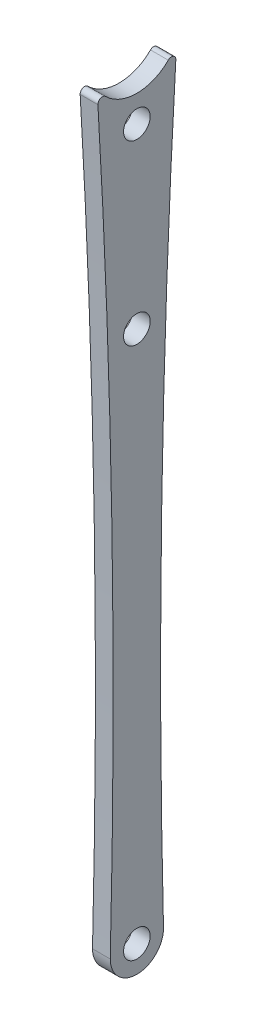
SolidWorks part; units mm, degrees
ref_plane "前视基准面" through (0, 0, 0) normal (0, 0, 1) x (1, 0, 0)
ref_plane "上视基准面" through (0, 0, 0) normal (0, 1, 0) x (1, 0, 0)
ref_plane "右视基准面" through (0, 0, 0) normal (1, 0, 0) x (0, 0, -1)
other "Configuration Table"
sketch "草图1" plane through (0, 0, 0) normal (1, 0, 0) x (0, 0, -1)
  line L0 (0, 0) -> (0, 88) construction
  arc A0 (-3, 0) -> (3, 0) centre (0, 0) ccw
  arc A1 (3, 0) -> (4.3906, 84.084) centre (1002.6743, 25.5202) cw
  arc A2 (4.3906, 84.084) -> (3.5377, 84.4667) centre (3.8915, 84.1133) ccw
  arc A3 (3.5377, 84.4667) -> (-3.5377, 84.4667) centre (0, 88) cw
  circle A4 centre (0, 80) radius 1.5
  circle A5 centre (0, 60) radius 1.5
  arc A6 (-4.3906, 84.084) -> (-3.5377, 84.4667) centre (-3.8915, 84.1133) cw
  arc A7 (-3, 0) -> (-4.3906, 84.084) centre (-1002.6743, 25.5202) ccw
  circle A8 centre (0, 0) radius 1.5
  dimension "D1" = 80
  dimension "D2" = 5
  dimension "D3" = 0.5
  dimension "D5" = 20
  dimension "D4" = 8
extrude "凸台-拉伸1" add sketch "草图1" along normal blind 2
